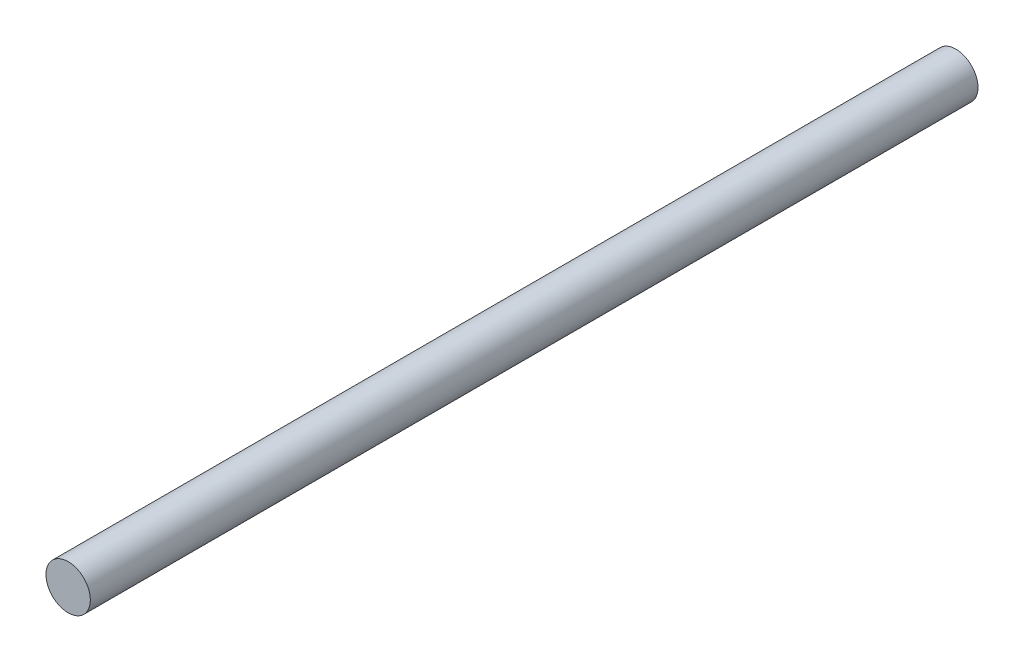
SolidWorks part; units mm, degrees
ref_plane "Alzado" through (0, 0, 0) normal (0, 0, 1) x (1, 0, 0)
ref_plane "Planta" through (0, 0, 0) normal (0, 1, 0) x (1, 0, 0)
ref_plane "Vista lateral" through (0, 0, 0) normal (1, 0, 0) x (0, 0, -1)
sketch "Croquis1" plane through (0, 0, 0) normal (0, 0, 1) x (1, 0, 0)
  circle A0 centre (0, 0) radius 4.75
  dimension "D1" = 9.5
extrude "Saliente-Extruir1" add sketch "Croquis1" along normal blind 190
